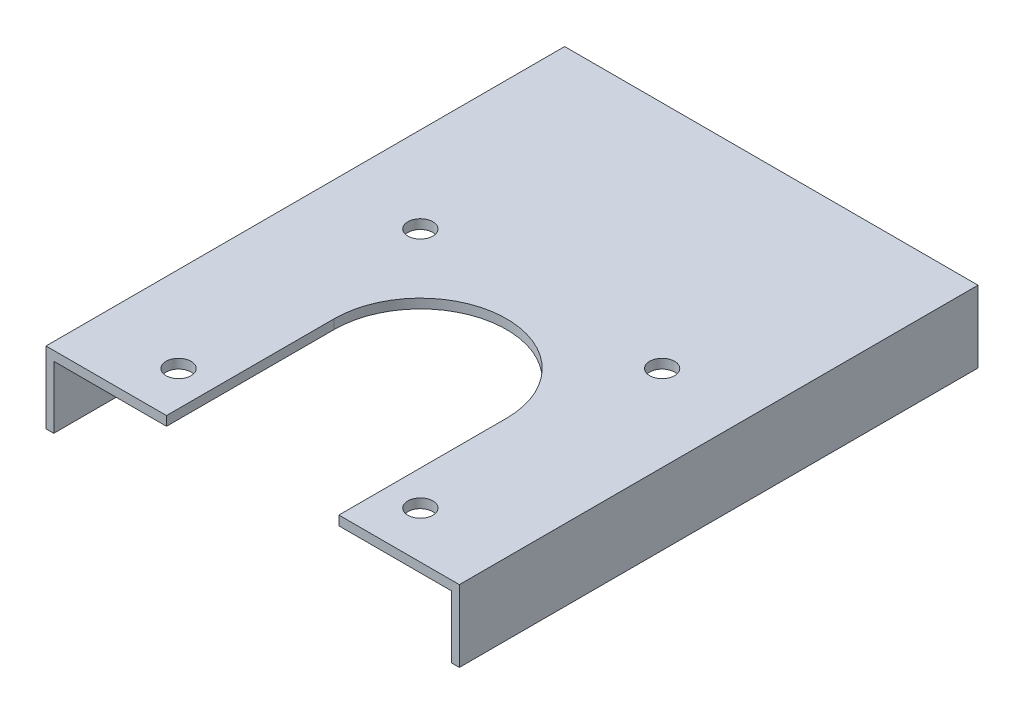
SolidWorks part; units mm, degrees
ref_plane "前视基准面" through (0, 0, 0) normal (0, 0, 1) x (1, 0, 0)
ref_plane "上视基准面" through (0, 0, 0) normal (0, 1, 0) x (1, 0, 0)
ref_plane "右视基准面" through (0, 0, 0) normal (1, 0, 0) x (0, 0, -1)
sketch "草图1" plane through (0, 0, 0) normal (0, 1, 0) x (1, 0, 0)
  line L0 (26.5, 0) -> (26.5, 66.5) construction
  line L1 (15.45, 0) -> (15.45, 21.5)
  line L2 (0, 0) -> (15.45, 0)
  line L3 (0, 0) -> (0, 66.5)
  line L4 (0, 66.5) -> (53, 66.5)
  line L5 (53, 0) -> (53, 66.5)
  line L6 (37.55, 0) -> (37.55, 21.5)
  line L7 (37.55, 0) -> (53, 0)
  line L8 (42, 6) -> (42, 37) construction
  line L9 (42, 21.5) -> (11, 21.5) construction
  arc A0 (15.45, 21.5) -> (37.55, 21.5) centre (26.5, 21.5) cw
  circle A1 centre (11, 6) radius 1.6
  circle A2 centre (11, 37) radius 1.6
  circle A3 centre (42, 37) radius 1.6
  circle A4 centre (42, 6) radius 1.6
  point P22 (26, 23.4791)
  point P23 (26, 21.5213)
  point P24 (0, 0)
  point P25 (0, 0)
  point P26 (26.4281, 21.5)
  dimension "D2" = 31
  dimension "D3" = 3.2
  dimension "D4" = 31
  dimension "D7" = 6
  dimension "D6" = 60.5
  dimension "D8" = 11.05
  dimension "D1" = 22.1
  dimension "D5" = 53
extrude "凸台-拉伸1" add sketch "草图1" along normal blind 1.2
sketch "草图2" plane through (0, 0, 0) normal (0, -1, 0) x (1, 0, 0)
  line L7 (1, 0) -> (1, -65.5)
  line L8 (0, 0) -> (15.45, 0) construction
  line L9 (1, -65.5) -> (52, -65.5)
  line L10 (52, -65.5) -> (52, 0)
  line L11 (37.55, 0) -> (53, 0) construction
  line L12 (52, 0) -> (53, 0)
  line L13 (53, 0) -> (53, -66.5) construction
  line L14 (53, 0) -> (53, -66.5)
  line L15 (53, -66.5) -> (0, -66.5)
  line L16 (0, -66.5) -> (0, 0)
  line L17 (0, 0) -> (1, 0)
  dimension "D1" = 1
  dimension "D2" = 1
  dimension "D3" = 1
extrude "凸台-拉伸2" add sketch "草图2" along normal blind 8
sketch "草图3" plane through (0, 0, -66.5) normal (0, 0, -1) x (-1, 0, 0)
  line L0 (-26.5, 1.2) -> (-26.5, -9.2) construction
  line L1 (-53, 1.2) -> (0, 1.2) construction
  line L3 (-53, -3.4) -> (0.7175, -3.4) construction
  line L4 (-53, 1.2) -> (-53, -8) construction
  line L5 (0, -8) -> (-53, -8) construction
  circle A1 centre (-11.5, -4) radius 1.6
  circle A2 centre (-41.5, -4) radius 1.6
  dimension "D1" = 3.2
  dimension "D2" = 4
  dimension "D3" = 30
extrude "切除-拉伸1" cut sketch "草图3" against normal blind 8
